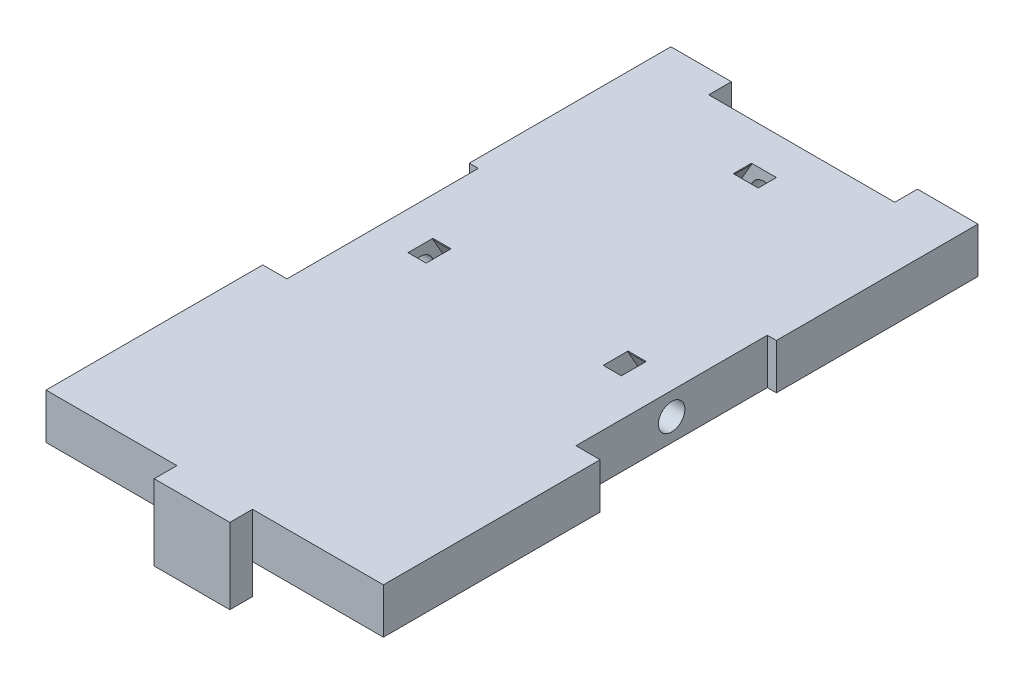
SolidWorks part; units mm, degrees
material "PP Copolymer"
ref_plane "Alzado" through (0, 0, 0) normal (0, 0, 1) x (1, 0, 0)
ref_plane "Planta" through (0, 0, 0) normal (0, 1, 0) x (1, 0, 0)
ref_plane "Vista lateral" through (0, 0, 0) normal (1, 0, 0) x (0, 0, -1)
sketch "Croquis1" plane through (0, 0, 0) normal (0, 1, 0) x (1, 0, 0)
  line L0 (-12.3, 40.3) -> (-12.3, 37.3)
  line L1 (-20.3, 40.3) -> (-12.3, 40.3)
  line L3 (-20.3, -40.3) -> (20.3, -40.3)
  line L5 (-20.3, 40.3) -> (20.3, -40.3) construction
  line L6 (-20.3, -40.3) -> (20.3, 40.3) construction
  line L7 (-12.3, 37.3) -> (12.3, 37.3)
  line L8 (12.3, 37.3) -> (12.3, 40.3)
  line L9 (12.3, 40.3) -> (20.3, 40.3)
  line L10 (0, 37.3) -> (0, 0) construction
  line L12 (19.1, 13.65) -> (19.1, -11.65)
  line L14 (19.1, 1) -> (-19.1, 1) construction
  line L15 (20.3, 13.65) -> (20.3, 40.3)
  line L17 (19.1, 13.65) -> (20.3, 13.65)
  line L18 (20.3, -11.65) -> (19.1, -11.65) construction
  line L19 (20.3, -11.65) -> (20.3, -40.3) construction
  line L20 (-20.3, -11.65) -> (-20.3, -40.3) construction
  line L21 (-20.3, -11.65) -> (-19.1, -11.65) construction
  line L22 (-19.1, 13.65) -> (-20.3, 13.65)
  line L24 (-20.3, 13.65) -> (-20.3, 40.3)
  line L25 (-19.1, 13.65) -> (-19.1, -11.65)
  line L26 (-20.3, -40.3) -> (-22.3, -40.3)
  line L27 (-22.3, -40.3) -> (-22.3, -11.65)
  line L28 (-22.3, -11.65) -> (-19.1, -11.65)
  line L30 (19.1, -11.65) -> (22.3, -11.65)
  line L31 (22.3, -11.65) -> (22.3, -40.3)
  line L32 (22.3, -40.3) -> (20.3, -40.3)
  point P0 (0, 0)
  point P22 (0, 1)
  dimension "D1" = 80.6
  dimension "D2" = 40.6
  dimension "D3" = 3
  dimension "D4" = 24.6
  dimension "D5" = 1.2
  dimension "D6" = 25.3
  dimension "D7" = 1
  dimension "D8" = 1.2
  dimension "D9" = 44.6
extrude "Saliente-Extruir1" add sketch "Croquis1" along normal blind 6
sketch "Croquis2" plane through (0, 0, 40.3) normal (0, 0, 1) x (1, 0, 0)
  line L0 (-22.3, 6) -> (22.3, 6) construction
  line L1 (-5, 6) -> (5, 6)
  line L2 (-5, 6) -> (-5, -4)
  line L3 (-5, -4) -> (5, -4)
  line L4 (5, 6) -> (5, -4)
  line L5 (0, 0) -> (0, 6) construction
  line L6 (-22.3, 0) -> (22.3, 0) construction
  dimension "D1" = 10
  dimension "D2" = 10
extrude "Saliente-Extruir2" add sketch "Croquis2" along normal blind 3
ref_plane "Plano4" through (0, 0, -32.3) normal (0, 0, -1) x (-1, 0, 0)
sketch "Croquis3" plane through (0, 0, -32.3) normal (0, 0, -1) x (-1, 0, 0)
  line L0 (1.5877, 5.75) -> (3.1754, 3) construction
  line L1 (-3.1754, 3) -> (-1.5877, 0.25) construction
  line L2 (1.5877, 5.75) -> (-1.5877, 5.75) construction
  line L3 (-1.5877, 5.75) -> (-3.1754, 3) construction
  line L4 (-1.5877, 0.25) -> (1.5877, 0.25) construction
  line L5 (1.5877, 0.25) -> (3.1754, 3) construction
  line L6 (1.5877, 0.25) -> (-1.5877, 5.75) construction
  line L7 (1.5877, 5.75) -> (-1.5877, 0.25) construction
  line L8 (3.1754, 3) -> (-3.1754, 3) construction
  line L9 (1.6454, 5.85) -> (3.2909, 3)
  line L10 (1.6454, 0.15) -> (3.2909, 3) construction
  line L11 (-1.6454, 0.15) -> (1.6454, 0.15) construction
  line L12 (-3.2909, 3) -> (-1.6454, 0.15) construction
  line L13 (-1.6454, 5.85) -> (-3.2909, 3)
  line L14 (1.6454, 5.85) -> (-1.6454, 5.85) construction
  line L17 (0, 6) -> (0, 0) construction
  line L18 (-12.3, 6) -> (12.3, 6) construction
  line L19 (3.2909, 3) -> (3.2909, 0)
  line L20 (-3.2909, 3) -> (-3.2909, 0)
  line L21 (5, 0) -> (-5, 0) construction
  line L22 (3.2909, 0) -> (-3.2909, 0)
  line L23 (-1.6454, 5.85) -> (-1.6454, 6)
  line L24 (1.6454, 5.85) -> (1.6454, 6)
  line L25 (1.6454, 6) -> (-1.6454, 6)
  point P3 (0, 3)
  point P13 (-1.6454, 6)
  dimension "D1" = 3.1754
  dimension "D2" = 5.5
  dimension "D3" = 0.1
extrude "Cortar-Extruir1" cut sketch "Croquis3" against normal blind 2.4
sketch "Croquis4" plane through (0, 0, -37.3) normal (0, 0, -1) x (-1, 0, 0)
  line L0 (-12.3, 0) -> (12.3, 0) construction
  circle A0 centre (0, 3) radius 1.75
  dimension "D1" = 3
  dimension "D2" = 3.5
extrude "Cortar-Extruir2" cut sketch "Croquis4" against normal up to next
sketch "Croquis5" [suppressed] plane through (0, 6, 0) normal (0, 1, 0) x (1, 0, 0)
  line L0 (20.3, -14.1) -> (19.1, -14.1) construction
  line L1 (19.1, 16.1) -> (17.1, 16.1)
  line L2 (19.1, 16.1) -> (19.1, -14.1)
  line L3 (19.1, -14.1) -> (17.1, -14.1)
  line L4 (17.1, 16.1) -> (17.1, -14.1)
  line L5 (0, 0) -> (0, -43.3) construction
  line L6 (5, -43.3) -> (-5, -43.3) construction
  line L7 (-17.1, 16.1) -> (-17.1, -14.1)
  line L8 (-19.1, -14.1) -> (-17.1, -14.1)
  line L9 (-19.1, 16.1) -> (-19.1, -14.1)
  line L10 (-19.1, 16.1) -> (-17.1, 16.1)
  dimension "D1" = 2
extrude "Cortar-Extruir3" [suppressed] cut sketch "Croquis5" against normal blind 3.2
ref_plane "Plano5" through (-14.1, 0, 0) normal (-1, 0, 0) x (0, 0, 1)
sketch "Croquis6" plane through (-14.1, 0, 0) normal (-1, 0, 0) x (0, 0, 1)
  line L0 (0.5877, 5.75) -> (2.1754, 3) construction
  line L1 (-4.1754, 3) -> (-2.5877, 0.25) construction
  line L2 (0.5877, 5.75) -> (-2.5877, 5.75) construction
  line L3 (-2.5877, 5.75) -> (-4.1754, 3) construction
  line L4 (-2.5877, 0.25) -> (0.5877, 0.25) construction
  line L5 (0.5877, 0.25) -> (2.1754, 3) construction
  line L6 (0.5877, 0.25) -> (-2.5877, 5.75) construction
  line L7 (0.5877, 5.75) -> (-2.5877, 0.25) construction
  line L8 (2.1754, 3) -> (-4.1754, 3) construction
  line L9 (0.6454, 5.85) -> (2.2909, 3)
  line L10 (0.6454, 0.15) -> (2.2909, 3) construction
  line L11 (-2.6454, 0.15) -> (0.6454, 0.15) construction
  line L12 (-4.2909, 3) -> (-2.6454, 0.15) construction
  line L13 (-2.6454, 5.85) -> (-4.2909, 3)
  line L14 (0.6454, 5.85) -> (-2.6454, 5.85) construction
  line L15 (-1, 6) -> (-1, 0) construction
  line L16 (2.2909, 3) -> (2.2909, 0)
  line L17 (-4.2909, 3) -> (-4.2909, 0)
  line L18 (2.2909, 0) -> (-4.2909, 0)
  line L19 (-2.6454, 5.85) -> (-2.6454, 6)
  line L20 (0.6454, 5.85) -> (0.6454, 6)
  line L21 (0.6454, 6) -> (-2.6454, 6)
  line L22 (-13.65, 0) -> (11.65, 0) construction
  line L23 (-1, 3) -> (-13.65, 3) construction
  line L27 (-1, 3) -> (11.65, 3) construction
  line L30 (-13.65, 6) -> (-13.65, 0) construction
  line L31 (11.65, 6) -> (11.65, 0) construction
  point P3 (-1, 3)
  point P21 (-2.2066, 3)
  point P23 (0, 0)
  point P24 (-13.3231, 3)
  point P29 (0, 0)
  dimension "D1" = 3.1754
  dimension "D2" = 5.5
  dimension "D3" = 0.1
  dimension "D4" = 3
  dimension "D5" = 3
extrude "Cortar-Extruir4" cut sketch "Croquis6" against normal blind 2.4
sketch "Croquis7" plane through (-19.1, 0, 0) normal (-1, 0, 0) x (0, 0, 1)
  circle A0 centre (-1, 3) radius 1.75
  dimension "D1" = 3.5
extrude "Cortar-Extruir5" cut sketch "Croquis7" against normal up to next
mirror "Simetría1" about plane through (0, 0, 0) normal (1, 0, 0) of "Cortar-Extruir4", "Cortar-Extruir5"
